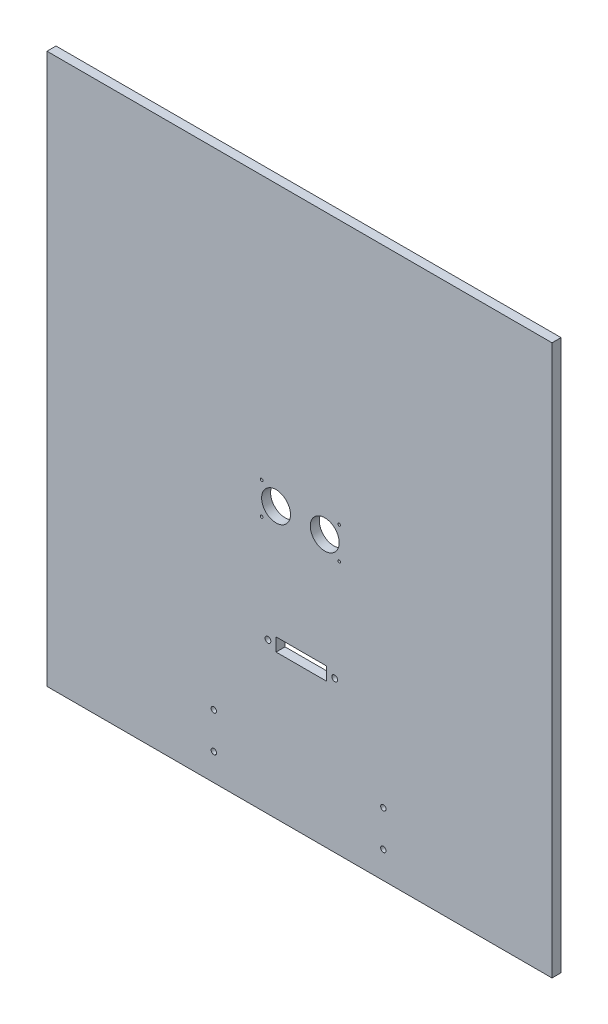
SolidWorks part; units mm, degrees
ref_plane "Plan de face" through (0, 0, 0) normal (0, 0, 1) x (1, 0, 0)
ref_plane "Plan de dessus" through (0, 0, 0) normal (0, 1, 0) x (1, 0, 0)
ref_plane "Plan de droite" through (0, 0, 0) normal (1, 0, 0) x (0, 0, -1)
sketch "Esquisse1" plane through (0, 0, 0) normal (0, 0, 1) x (1, 0, 0)
  line L1 (0, 0) -> (280, 0)
  line L2 (0, 0) -> (0, 305)
  line L3 (0, 305) -> (280, 305)
  line L4 (280, 0) -> (280, 305)
  dimension "D1" = 305
  dimension "D2" = 280
extrude "Boss.-Extru.1" add sketch "Esquisse1" along normal blind 5
sketch "Esquisse2" plane through (0, 0, 5) normal (0, 0, 1) x (1, 0, 0)
  circle A0 centre (92.5, 35) radius 1.5
  circle A1 centre (92.5, 15) radius 1.5
  circle A2 centre (186.5, 35) radius 1.5
  circle A3 centre (186.5, 15) radius 1.5
  dimension "D1" = 3
  dimension "D2" = 3
  dimension "D3" = 3
  dimension "D4" = 3
extrude "Enlèv. mat.-Extru.1" cut sketch "Esquisse2" against normal through all
sketch "Esquisse3" plane through (0, 0, 5) normal (0, 0, 1) x (1, 0, 0)
  circle A0 centre (187.5, 758.8055) radius 1.5
  circle A1 centre (187.5, 778.8055) radius 1.5
  circle A2 centre (93.5, 758.8055) radius 1.5
  circle A3 centre (93.5, 778.8055) radius 1.5
  circle A4 centre (187.5, 778.8055) radius 1.5 construction
  dimension "D1" = 3
  dimension "D2" = 3
  dimension "D3" = 3
  dimension "D4" = 3
  dimension "D5" = 0
extrude "Enlèv. mat.-Extru.2" cut sketch "Esquisse3" against normal through all
sketch "Esquisse4" plane through (0, 0, 0) normal (0, 0, -1) x (-1, 0, 0)
  line L0 (0, 0) -> (-280, 0) construction
  line L1 (-155, 87.3) -> (-127, 87.3)
  line L2 (-155, 87.3) -> (-155, 80)
  line L3 (-155, 80) -> (-127, 80)
  line L4 (-127, 87.3) -> (-127, 80)
  line L5 (-280, 0) -> (-280, 305) construction
  line L6 (-180.5491, 83.65) -> (-87.7218, 83.65) construction
  circle A0 centre (-159.5, 83.65) radius 1.6
  circle A1 centre (-122.5, 83.65) radius 1.6
  point P4 (-141, 80)
  point P9 (-155, 83.65)
  dimension "D6" = 3.2
  dimension "D7" = 3.2
  dimension "D8" = 4.5
  dimension "D1" = 7.3
  dimension "D2" = 28
  dimension "D3" = 80
  dimension "D4" = 125
  dimension "D5" = 3.65
  dimension "D9" = 4.5
extrude "Enlèv. mat.-Extru.3" cut sketch "Esquisse4" against normal through all
sketch "Esquisse5" plane through (0, 0, 0) normal (0, 0, -1) x (-1, 0, 0)
  line L0 (0, 305) -> (0, 0) construction
  line L1 (-118, 160) -> (-163, 160) construction
  line L2 (0, 0) -> (-280, 0) construction
  line L3 (-163, 160) -> (-163, 140) construction
  line L4 (-163, 140) -> (-118, 140) construction
  line L5 (-118, 140) -> (-118, 160) construction
  line L6 (0, 305) -> (0, 0) construction
  circle A0 centre (-154, 150) radius 8
  circle A1 centre (-127, 150) radius 8
  circle A2 centre (-119, 158.7) radius 0.75
  circle A3 centre (-162, 158.7) radius 0.75
  circle A4 centre (-162, 141) radius 0.75
  circle A5 centre (-119, 141) radius 0.75
  dimension "D1" = 16
  dimension "D2" = 16
  dimension "D3" = 27
  dimension "D4" = 127
  dimension "D5" = 150
  dimension "D6" = 150
  dimension "D7" = 20
  dimension "D8" = 45
  dimension "D9" = 10
  dimension "D10" = 9
  dimension "D11" = 1.5
  dimension "D12" = 1.5
  dimension "D13" = 1.5
  dimension "D14" = 1.5
  dimension "D15" = 1
  dimension "D16" = 1
  dimension "D17" = 1
  dimension "D18" = 1.3
  dimension "D19" = 1.3
  dimension "D20" = 1
  dimension "D21" = 1
  dimension "D22" = 1
extrude "Enlèv. mat.-Extru.4" cut sketch "Esquisse5" against normal through all
